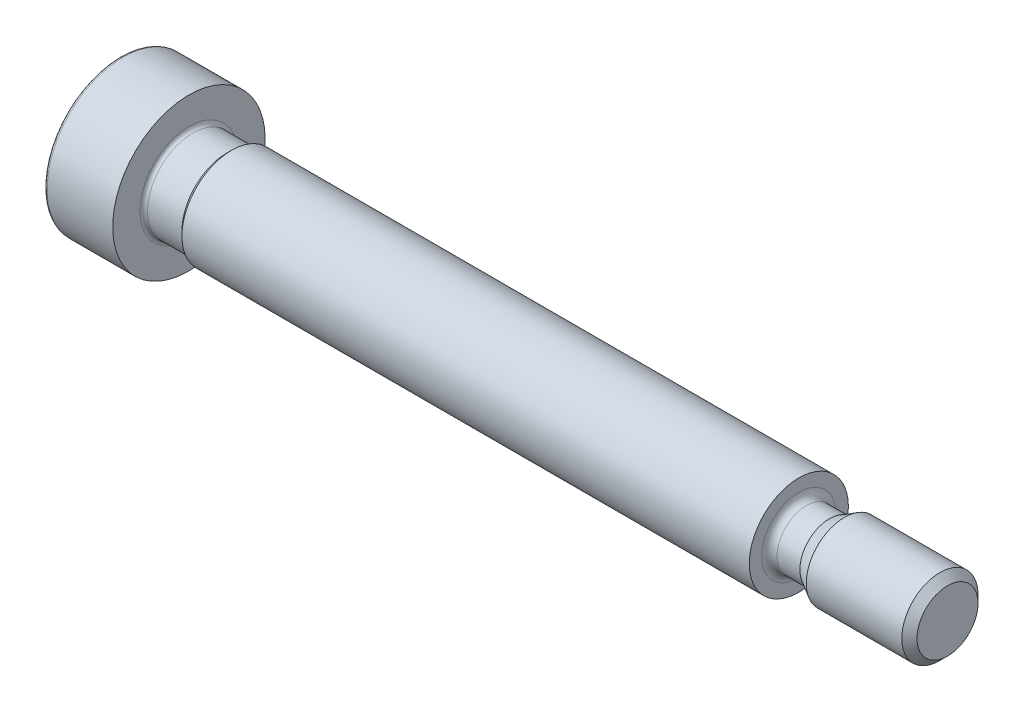
SolidWorks part; units mm, degrees
ref_plane "Front" through (0, 0, 0) normal (0, 0, 1) x (1, 0, 0)
ref_plane "Top" through (0, 0, 0) normal (0, 1, 0) x (1, 0, 0)
ref_plane "Right" through (0, 0, 0) normal (1, 0, 0) x (0, 0, -1)
sketch "Sketch1" plane through (0, 0, 0) normal (1, 0, 0) x (0, 0, -1)
  circle A0 centre (0, 0) radius 5
  dimension "dk" = 10
extrude "BaseHead" add sketch "Sketch1" along normal blind 4.5
sketch "Sketch2" plane through (4.5, 0, 0) normal (1, 0, 0) x (0, 0, -1)
  circle A0 centre (0, 0) radius 3.25
  dimension "ds" = 6.5
extrude "BaseBody" add sketch "Sketch2" along normal blind 40
sketch "Sketch3" plane through (44.5, 0, 0) normal (1, 0, 0) x (0, 0, -1)
  circle A0 centre (0, 0) radius 2.5
  dimension "d" = 5
extrude "BaseEnd" add sketch "Sketch3" along normal blind 9.75
cosmetic thread "ThreadCosmetic1" parameters "THD_MINOR"=4.134
sketch "Sketch4" plane through (-14.7581, 7.8281, 0) normal (0, 0, 1) x (0, -1, 0)
  line L0 (7.8281, 27.7861) -> (7.8281, 17.3801) construction
  line L1 (0.8981, 61.2581) -> (3.8981, 61.2581)
  line L2 (0.8981, 61.2581) -> (0.8981, 59.2581)
  line L3 (0.8981, 59.2581) -> (5.8981, 59.2581)
  line L4 (5.8981, 61.2581) -> (5.8981, 59.2581)
  line L7 (5.8981, 61.2581) -> (3.8981, 64.7222)
  line L8 (3.8981, 64.7222) -> (3.8981, 61.2581)
  line L9 (11.0781, 59.2581) -> (4.5781, 59.2581) construction
  dimension "g2" = 2
  dimension "dg2" = 3.86
  dimension "D3" = 5
  dimension "D1" = 30
  dimension "D2" = 2
revolve "Cut-Revolve2" cut sketch "Sketch4" angle 360 about L0
fillet "Fillet1" radius 0.5 1 edges at (44.5, 1.93, 0)
sketch "Sketch5" plane through (0, 0, 0) normal (1, 0, 0) x (0, 0, -1)
  line L1 (1.7321, 0) -> (0.866, 1.5)
  line L2 (0.866, 1.5) -> (-0.866, 1.5)
  line L3 (-0.866, 1.5) -> (-1.7321, 0)
  line L4 (-1.7321, 0) -> (-0.866, -1.5)
  line L5 (-0.866, -1.5) -> (0.866, -1.5)
  line L6 (0.866, -1.5) -> (1.7321, 0)
  circle A0 centre (0, 0) radius 1.5 construction
  dimension "s" = 3
extrude "Socket" cut sketch "Sketch5" along normal blind 2.4
sketch "Sketch6" plane through (2.4, 0, 0) normal (-1, 0, 0) x (0, 0, 1)
  line L0 (1.7321, 0) -> (0.866, -1.5) construction
  line L1 (0.866, -1.5) -> (-0.866, -1.5) construction
  line L2 (-0.866, -1.5) -> (-1.7321, 0) construction
  line L3 (0.866, 1.5) -> (1.7321, 0) construction
  line L4 (-1.7321, 0) -> (-0.866, 1.5) construction
  line L5 (-0.866, 1.5) -> (0.866, 1.5) construction
  line L6 (1.7321, 0) -> (0.866, -1.5)
  line L7 (0.866, -1.5) -> (-0.866, -1.5)
  line L8 (-0.866, -1.5) -> (-1.7321, 0)
  line L9 (0.866, 1.5) -> (1.7321, 0)
  line L10 (-1.7321, 0) -> (-0.866, 1.5)
  line L11 (-0.866, 1.5) -> (0.866, 1.5)
extrude "Cut-Extrude2" cut sketch "Sketch6" against normal blind 10 draft 60
sketch "Sketch7" plane through (-6.2703, -1.6897, 0) normal (0, 0, 1) x (0, -1, 0)
  line L1 (-9.6497, 10.7703) -> (-4.8997, 10.7703)
  line L2 (-9.6497, 10.7703) -> (-9.6497, 13.2703)
  line L3 (-9.6497, 13.2703) -> (-7.6497, 13.2703)
  line L4 (-4.6497, 11.0203) -> (-4.6497, 13.2703)
  line L5 (-1.6897, 18.8023) -> (-1.6897, 7.3187) construction
  line L7 (-4.6497, 13.2703) -> (-6.6497, 15.2703)
  line L8 (-6.6497, 15.2703) -> (-7.6497, 15.2703)
  line L9 (-7.6497, 15.2703) -> (-7.6497, 13.2703)
  line L10 (3.3103, 10.7703) -> (-6.6897, 10.7703) construction
  arc A0 (-4.8997, 10.7703) -> (-4.6497, 11.0203) centre (-4.8997, 11.0203) ccw
  dimension "r1" = 0.25
  dimension "D1" = 45
  dimension "dg1" = 5.92
  dimension "D2" = 5
  dimension "g1" = 2.5
  dimension "D3" = 2
  dimension "D4" = 1
revolve "Neck" cut sketch "Sketch7" angle 360 about L5
chamfer "Chamfer1" distance 0.5 angle 45 1 edges at (54.25, 0, -2.5)
fillet "HeadFillet" radius 0.2 1 edges at (0, 0, -5)
sketch "Sketch8" plane through (0, 0, 0) normal (0, 0, 1) x (1, 0, 0)
  line L0 (53.75, 2.125) -> (53.9665, 2.5)
  line L1 (53.9665, 2.5) -> (53.9665, 2.933)
  line L2 (53.9665, 2.933) -> (53.5335, 2.933)
  line L3 (53.5335, 2.933) -> (53.5335, 2.5)
  line L4 (53.5335, 2.5) -> (53.75, 2.125)
  line L5 (53.75, -2.5) -> (53.75, 2.5) construction
  line L6 (0, 0) -> (37.4968, 0) construction
  dimension "D1" = 5
  dimension "D2" = 0.433
revolve "Cut-Revolve10" [suppressed] cut sketch "Sketch8" angle 360 about L6
pattern_linear "LPattern10" [suppressed] count 15 spacing 0.5196 along (1, 0, 0)
equation "\"D1@Sketch8\" = \"d@Sketch3\""
equation "\"D2@Sketch8\" =  ( \"d@Sketch3\" - \"THD_MINOR@ThreadCosmetic1\" )  / 2"
equation "\"D3@LPattern10\" = \"D2@Sketch8\" * 1.2"
equation "\"D1@LPattern10\" =  ( \"b@BaseEnd\" - \"g2@Sketch4\" )  / \"D3@LPattern10\""
